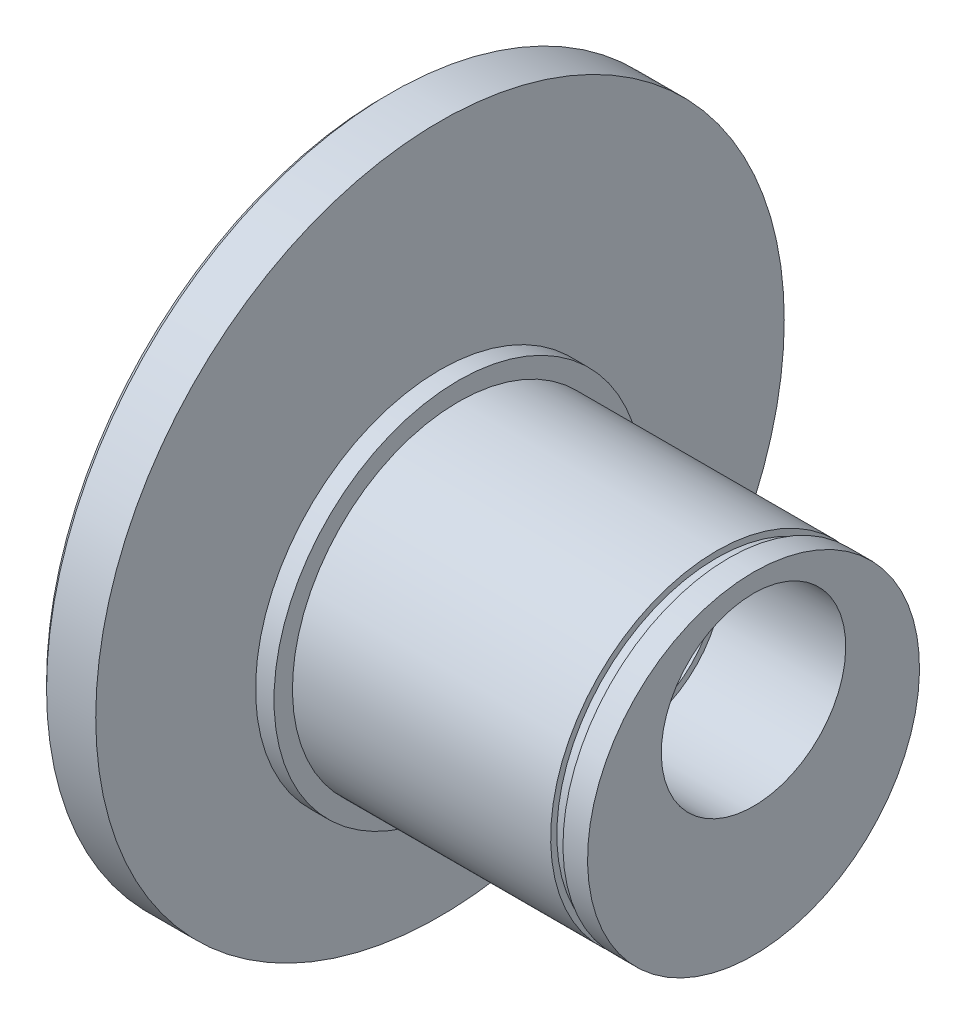
SolidWorks part; units mm, degrees
ref_plane "Plan de face" through (0, 0, 0) normal (0, 0, 1) x (1, 0, 0)
ref_plane "Plan de dessus" through (0, 0, 0) normal (0, 1, 0) x (1, 0, 0)
ref_plane "Plan de droite" through (0, 0, 0) normal (1, 0, 0) x (0, 0, -1)
sketch "Esquisse1" plane through (0, 0, 0) normal (0, 0, 1) x (1, 0, 0)
  line L0 (0, 0) -> (108.1761, 0) construction
  line L1 (0, 0) -> (0, 35)
  line L2 (0, 35) -> (5, 35)
  line L3 (5, 35) -> (5, 55)
  line L4 (5, 55) -> (6, 56)
  line L5 (6, 56) -> (14, 56)
  line L6 (14, 56) -> (14, 0)
  line L7 (0, 0) -> (14, 0)
  dimension "D1" = 35
  dimension "D2" = 5
  dimension "D3" = 20
  dimension "D4" = 45
  dimension "D5" = 1
  dimension "D6" = 8
revolve "Révolution1" add sketch "Esquisse1" angle 360 about L0
sketch "Esquisse2" plane through (0, 0, 0) normal (-1, 0, 0) x (0, 0, 1)
  circle A0 centre (0, 0) radius 24.5
  dimension "D1" = 49
extrude "Enlèv. mat.-Extru.1" cut sketch "Esquisse2" against normal blind 10
sketch "Esquisse3" plane through (0, 0, 0) normal (0, 0, 1) x (1, 0, 0)
  line L0 (58.5999, -9) -> (-9.8795, -9) construction
  line L1 (14, 21) -> (17, 21)
  line L2 (14, -56) -> (14, 56) construction
  line L3 (17, 21) -> (17, 18)
  line L4 (17, 18) -> (59, 18)
  line L5 (59, 18) -> (59, 17)
  line L6 (59, 17) -> (61, 17)
  line L7 (61, 17) -> (61, 18)
  line L8 (61, 18) -> (65, 18)
  line L9 (65, 18) -> (65, -9)
  line L10 (65, -9) -> (14, -9)
  line L11 (14, -9) -> (14, 21)
  point P7 (0, 0)
  dimension "D1" = 9
  dimension "D2" = 30
  dimension "D3" = 3
  dimension "D4" = 3
  dimension "D5" = 42
  dimension "D6" = 1
  dimension "D7" = 2
  dimension "D8" = 1
  dimension "D9" = 4
revolve "Révolution2" add sketch "Esquisse3" angle 360 about L0
sketch "Esquisse4" plane through (10, 0, 0) normal (-1, 0, 0) x (0, 0, 1)
  circle A0 centre (0, 0) radius 14
  dimension "D1" = 28
extrude "Enlèv. mat.-Extru.2" cut sketch "Esquisse4" against normal through all
sketch "Esquisse5" plane through (10, 0, 0) normal (-1, 0, 0) x (0, 0, 1)
  circle A0 centre (0, 0) radius 15
  dimension "D1" = 30
extrude "Enlèv. mat.-Extru.3" cut sketch "Esquisse5" against normal blind 20
sketch "Esquisse6" plane through (65, 0, 0) normal (1, 0, 0) x (0, 0, -1)
  circle A0 centre (0, 0) radius 15
  circle A1 centre (0, 0) radius 14 construction
  dimension "D1" = 30
extrude "Enlèv. mat.-Extru.4" cut sketch "Esquisse6" against normal blind 20
